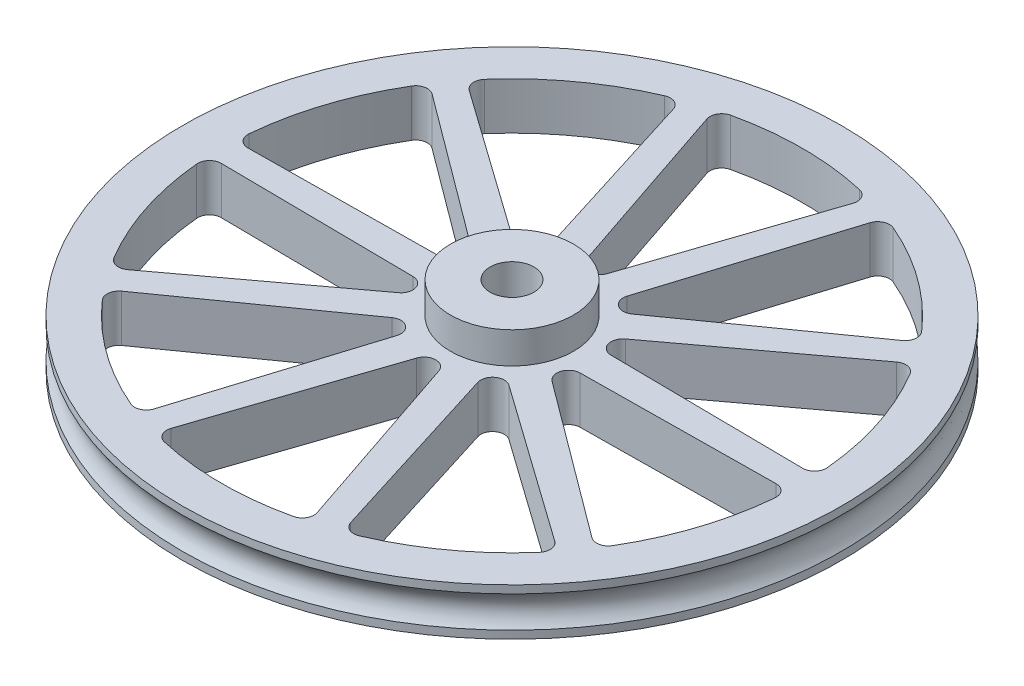
SolidWorks part; units mm, degrees
ref_plane "Front Plane" through (0, 0, 0) normal (0, 0, 1) x (1, 0, 0)
ref_plane "Top Plane" through (0, 0, 0) normal (0, 1, 0) x (1, 0, 0)
ref_plane "Right Plane" through (0, 0, 0) normal (1, 0, 0) x (0, 0, -1)
ref_plane "Plane1" through (0, -2, 0) normal (0, 1, 0) x (1, 0, 0)
sketch "Sketch2" plane through (0, 0, 0) normal (0, 0, 1) x (1, 0, 0)
  line L0 (0, 0) -> (0, 21.0224) construction
  line L1 (2.8412, -5) -> (7.8412, -5)
  line L2 (2.794, 0) -> (2.794, 5)
  line L3 (2.794, 5) -> (7.8412, 5)
  line L4 (7.8412, -5) -> (7.8412, 5)
  line L5 (0, 0) -> (78.4279, 0) construction
  line L6 (42, -4) -> (42, -5)
  line L7 (37, 1) -> (42, 1)
  line L8 (37, 1) -> (37, -5)
  line L9 (37, -5) -> (42, -5)
  line L10 (42, 1) -> (42, 0)
  line L12 (0, -55) -> (0, 55) construction
  line L16 (2.8412, -5) -> (1.5, -5)
  line L18 (2.794, 0) -> (1.5, 0)
  line L19 (1.5, -5) -> (1.5, 0)
  line L20 (55, 0) -> (-55, 0) construction
  spline S0 degree 2 poles (42, 0) (40.4125, -2) (42, -4) knots 0 0 0 1 1 1
  point P5 (7.8412, 0)
  point P34 (37, -2)
  dimension "D1" = 5
  dimension "D2" = 1.5
  dimension "D3" = 2.794
  dimension "D4" = 42
  dimension "D5" = 5
  dimension "D6" = 1
  dimension "D7" = 6
  dimension "D8" = 1
  dimension "D9" = 0.7937
  dimension "D10" = 10
  dimension "D11" = 5
  dimension "D12" = 7.8412
revolve "Revolve1" add sketch "Sketch2" angle 360 about L0
sketch "Sketch3" plane through (0, -2, 0) normal (0, 1, 0) x (1, 0, 0)
  line L0 (7.5819, 2) -> (36.9619, 1.6795)
  line L1 (-55, 0) -> (55, 0) construction
  line L2 (7.5819, -2) -> (36.9619, -1.6795)
  circle A0 centre (0, 0) radius 7.8412 construction
  circle A1 centre (0, 0) radius 37 construction
  arc A2 (36.9619, -1.6795) -> (36.9619, 1.6795) centre (0, 0) ccw
  arc A3 (7.5819, -2) -> (7.5819, 2) centre (0, 0) ccw
  dimension "D1" = 1.25
  dimension "D2" = 4
extrude "Boss-Extrude1" add sketch "Sketch3" along normal mid plane 6
pattern_circular "CirPattern1" count 10 over 360 about axis through (0, 0, 0) along (0, 1, 0) of "Boss-Extrude1"
sketch "Sketch4" plane through (0, -2, 0) normal (0, 1, 0) x (1, 0, 0)
  line L14 (4.9583, -6.0745) -> (28.9156, -23.0844) construction
  line L15 (13.0191, -34.6338) -> (4.245, -6.5927) construction
  line L18 (4.9583, -6.0745) -> (7.4619, -7.8521)
  line L19 (13.0191, -34.6338) -> (12.5346, -33.0853)
  line L20 (5.162, -9.5231) -> (4.245, -6.5927)
  line L21 (27.5926, -22.145) -> (28.9156, -23.0844)
  circle A19 centre (0, 0) radius 7.8412 construction
  arc A21 (4.245, -6.5927) -> (4.9583, -6.0745) centre (0, 0) ccw
  arc A23 (27.8534, -24.3555) -> (27.5926, -22.145) centre (26.7242, -23.3681) ccw
  arc A24 (14.5563, -34.0164) -> (12.5346, -33.0853) centre (13.9662, -32.6373) cw
  arc A25 (5.162, -9.5231) -> (7.4619, -7.8521) centre (6.5935, -9.0752) cw
  arc A26 (13.0191, -34.6338) -> (28.9156, -23.0844) centre (0, 0) ccw construction
  arc A27 (13.0191, -34.6338) -> (14.5563, -34.0164) centre (0, 0) ccw
  arc A28 (27.8534, -24.3555) -> (28.9156, -23.0844) centre (0, 0) ccw
  dimension "D1" = 1.5
extrude "Boss-Extrude2" add sketch "Sketch4" along normal mid plane 6
pattern_circular "CirPattern3" count 10 over 360 about axis through (0, 0, 0) along (0, 1, 0) of "Boss-Extrude2"
